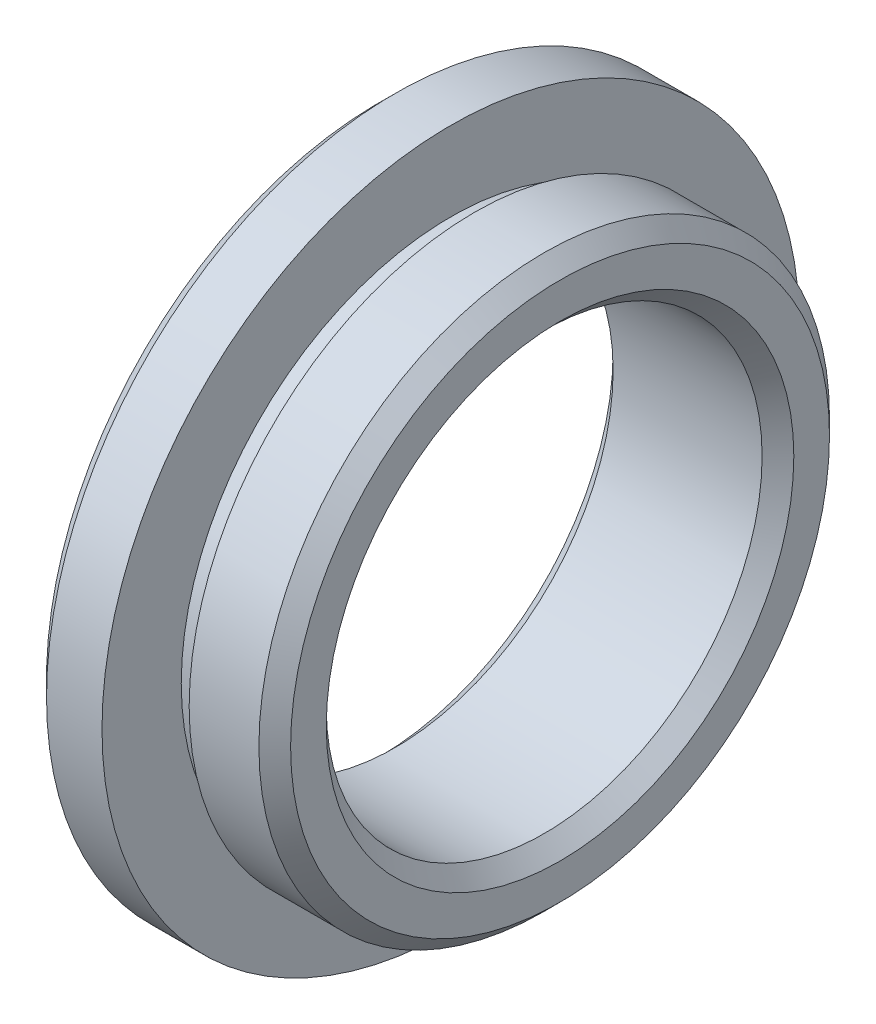
SolidWorks part; units mm, degrees
material "Acier non allié"
ref_plane "Face" through (0, 0, 0) normal (0, 0, 1) x (1, 0, 0)
ref_plane "Dessus" through (0, 0, 0) normal (0, 1, 0) x (1, 0, 0)
ref_plane "Droite" through (0, 0, 0) normal (1, 0, 0) x (0, 0, -1)
sketch "Esquisse1" plane through (0, 0, 0) normal (0, 0, 1) x (1, 0, 0)
  line L0 (0, 0) -> (61.2566, 0) construction
  line L1 (0, 13.75) -> (0, 22)
  line L2 (0, 22) -> (4.5, 22)
  line L3 (4.5, 22) -> (4.5, 17)
  line L4 (4.5, 17) -> (6, 17)
  line L5 (6, 17) -> (6, 18)
  line L6 (6, 18) -> (11.4, 18)
  line L7 (11.4, 18) -> (11.4, 13.75)
  line L8 (11.4, 13.75) -> (0, 13.75)
  dimension "D1" = 27.5
  dimension "D2" = 36
  dimension "D3" = 44
  dimension "D4" = 4.5
  dimension "D5" = 6.9
  dimension "D6" = 1.5
  dimension "D7" = 1
revolve "Révolution1" add sketch "Esquisse1" angle 360 about L0
cosmetic thread "Représentation de filetage1" parameters "D2"=34
chamfer "Chanfrein1" distance 1 angle 45 4 edges at (0, 0, 13.75) (11.4, 0, 13.75) (0, 0, 22) (11.4, 0, 18)
hole_wizard "Diamètre du perçage Ø3.1 (3.1)1" positions "Esquisse3D1" profile "Esquisse3" hole size "Ø3.1" standard "ISO"
sketch3d "Esquisse3D1"
  circle A0 centre (0, 0, 0) radius 14.75 construction
  point P0 (0, 18.5, 0)
  point P5 (14.75, 0, 0)
  dimension "D1" = 18.5
sketch "Esquisse3" plane through (0, 18.5, 0) normal (0, 1, 0) x (0, 0, 1)
  line L0 (0, 0) -> (0, 4.4313)
  line L1 (0, 4.4313) -> (1.55, 3.5)
  line L2 (1.55, 3.5) -> (1.55, 0)
  line L5 (1.55, 0) -> (0, 0)
  line L10 (0, 4.4313) -> (-1.55, 3.5) construction
  line L11 (0, -6.35) -> (0, 107.95) construction
  dimension "Diamètre du perçage" = 3.1
  dimension "Profondeur du perçage" = 3.5
  dimension "Angle de pointe" = 118
mirror "Symétrie1" about plane through (0, 0, 0) normal (0, 1, 0) of "Diamètre du perçage Ø3.1 (3.1)1"
